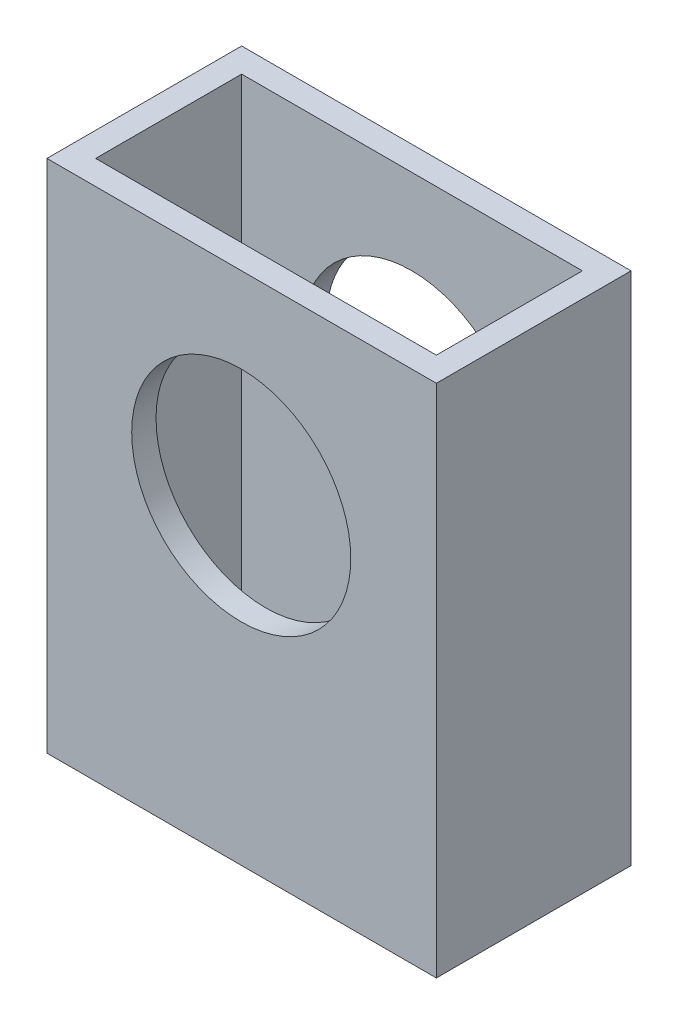
SolidWorks part; units mm, degrees
ref_plane "Front Plane" through (0, 0, 0) normal (0, 0, 1) x (1, 0, 0)
ref_plane "Top Plane" through (0, 0, 0) normal (0, 1, 0) x (1, 0, 0)
ref_plane "Right Plane" through (0, 0, 0) normal (1, 0, 0) x (0, 0, -1)
sketch "Sketch1" plane through (0, 0, 0) normal (0, 0, 1) x (1, 0, 0)
  line L1 (-990.7207, 634.9497) -> (-939.9207, 634.9497)
  line L2 (-990.7207, 634.9497) -> (-990.7207, 542.3575)
  line L3 (-990.7207, 542.3575) -> (-939.9207, 542.3575)
  line L4 (-939.9207, 634.9497) -> (-939.9207, 542.3575)
  line L10 (-990.7207, 542.3575) -> (-939.9207, 542.3575)
  line L11 (-990.7207, 542.3575) -> (-990.7207, 567.7575)
  line L12 (-990.7207, 567.7575) -> (-939.9207, 567.7575)
  line L13 (-939.9207, 542.3575) -> (-939.9207, 567.7575)
  circle A0 centre (-965.3752, 609.5497) radius 14.2875
  dimension "D2" = 25.4
  dimension "D1" = 50.8
extrude "Boss-Extrude1" add sketch "Sketch1" along normal blind 25.4 contours L2 L12 L4 L1 A0
sketch "Sketch2" plane through (0, 634.9497, 0) normal (0, 1, 0) x (1, 0, 0)
  line L0 (-990.7207, -25.4) -> (-990.7207, 0) construction
  line L1 (-987.5457, -22.225) -> (-943.0957, -22.225)
  line L2 (-987.5457, -22.225) -> (-987.5457, -3.175)
  line L3 (-987.5457, -3.175) -> (-943.0957, -3.175)
  line L4 (-943.0957, -22.225) -> (-943.0957, -3.175)
  line L5 (-990.7207, -25.4) -> (-939.9207, -25.4) construction
  line L6 (-939.9207, -25.4) -> (-939.9207, 0) construction
  point P4 (-944.5823, -2.5803)
  dimension "D1" = 3.175
  dimension "D2" = 3.175
  dimension "D3" = 3.175
  dimension "D4" = 3.175
extrude "Cut-Extrude1" cut sketch "Sketch2" against normal through all
